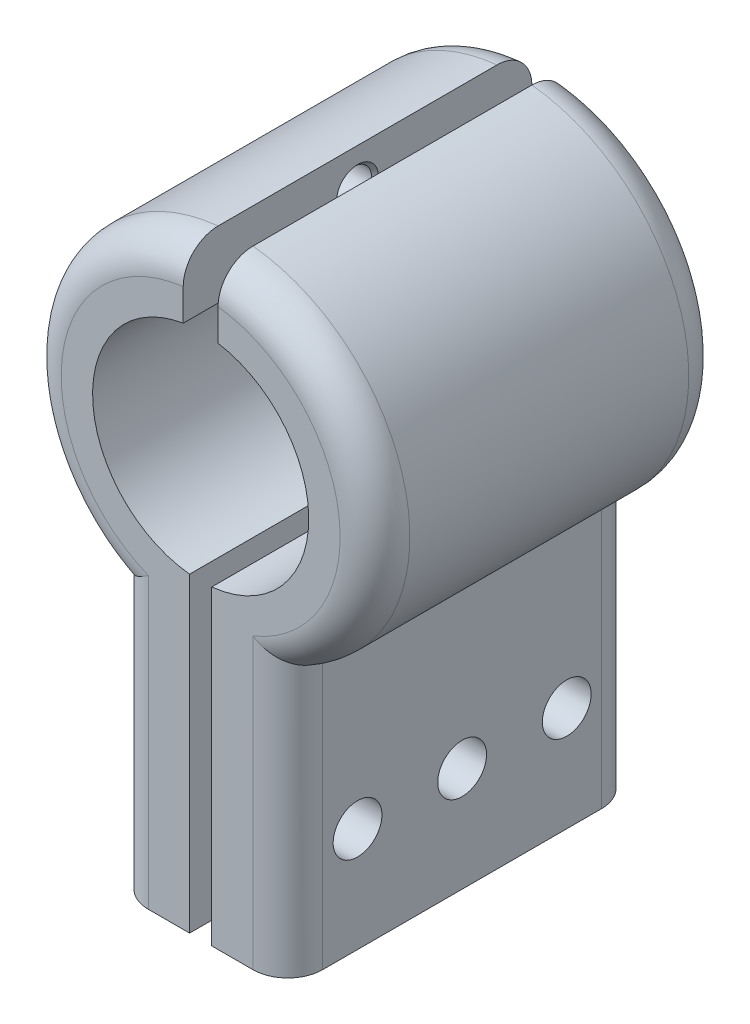
SolidWorks part; units mm, degrees
ref_plane "Front Plane" through (0, 0, 0) normal (0, 0, 1) x (1, 0, 0)
ref_plane "Top Plane" through (0, 0, 0) normal (0, 1, 0) x (1, 0, 0)
ref_plane "Right Plane" through (0, 0, 0) normal (1, 0, 0) x (0, 0, -1)
sketch "Sketch1" plane through (0, 0, 0) normal (0, 0, 1) x (1, 0, 0)
  line L0 (0, -60) -> (0, 0) construction
  line L2 (-12.5, -21.6506) -> (-12.5, -60)
  line L3 (-12.5, -60) -> (-1.59, -60)
  line L4 (12.5, -21.6506) -> (12.5, -60)
  line L5 (-2.5, 15.2971) -> (2.5, 15.2971) construction
  line L7 (-2.5, 24.8747) -> (-2.5, 15.2971)
  line L9 (2.5, 24.8747) -> (2.5, 15.2971)
  line L10 (0, 15.2971) -> (0, 0) construction
  line L11 (-1.59, -15.4182) -> (-1.59, -60)
  line L12 (1.59, -60) -> (1.59, -15.4182)
  line L13 (1.59, -60) -> (12.5, -60)
  line L14 (-1.59, -60) -> (1.59, -60) construction
  arc A0 (-2.5, 15.2971) -> (-1.59, -15.4182) centre (0, 0) ccw
  arc A1 (12.5, -21.6506) -> (2.5, 24.8747) centre (0, 0) ccw
  arc A2 (-2.5, 24.8747) -> (-12.5, -21.6506) centre (0, 0) ccw
  arc A3 (1.59, -15.4182) -> (2.5, 15.2971) centre (0, 0) ccw
  dimension "D1" = 31
  dimension "D2" = 25
  dimension "D3" = 5
  dimension "D4" = 25
  dimension "D5" = 3.18
  dimension "D6" = 60
extrude "Boss-Extrude1" add sketch "Sketch1" along normal mid plane 50
fillet "Fillet1" radius 5 4 edges at (-24.4418, 5.2534, 25) (-24.4418, 5.2534, -25) (-12.5, -40.8253, 25) (-12.5, -40.8253, -25)
fillet "Fillet2" radius 5 4 edges at (24.4418, 5.2534, -25) (12.5, -40.8253, -25) (12.5, -40.8253, 25) (24.4418, 5.2534, 25)
sketch "Sketch3" plane through (-12.5, 0, 0) normal (-1, 0, 0) x (0, 0, 1)
  line L0 (0, 0) -> (0, -45) construction
  line L1 (-15, -45) -> (15, -45) construction
  circle A0 centre (0, -45) radius 3.5
  circle A1 centre (-15, -45) radius 3.5
  circle A2 centre (15, -45) radius 3.5
  point P6 (0, -45)
  dimension "D1" = 7
  dimension "D3" = 30
  dimension "D2" = 45
extrude "Cut-Extrude1" cut sketch "Sketch3" against normal through all both and the other way through all
sketch "Sketch4" plane through (0, 0, 0) normal (1, 0, 0) x (0, 0, -1)
  line L0 (0, 19.5) -> (0, 0) construction
  circle A0 centre (0, 19.5) radius 2.5
  dimension "D1" = 19.5
  dimension "D2" = 5
extrude "Cut-Extrude2" cut sketch "Sketch4" against normal mid plane 16
chamfer "Chamfer1" distance 0.5 angle 45 2 edges at (-2.5, 17, 0) (-8, 19.5, -2.5)
chamfer "Chamfer2" distance 0.5 angle 45 2 edges at (8, 19.5, -2.5) (2.5, 22, 0)
